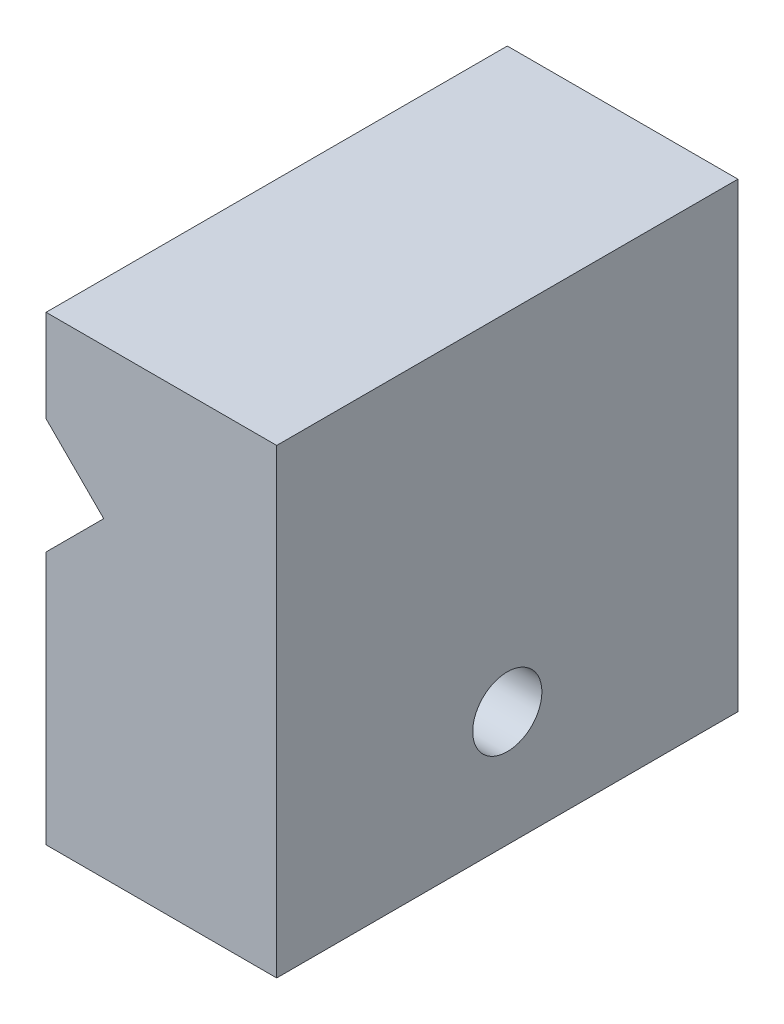
SolidWorks part; units mm, degrees
ref_plane "Plan de face" through (0, 0, 0) normal (0, 0, 1) x (1, 0, 0)
ref_plane "Plan de dessus" through (0, 0, 0) normal (0, 1, 0) x (1, 0, 0)
ref_plane "Plan de droite" through (0, 0, 0) normal (1, 0, 0) x (0, 0, -1)
sketch "Esquisse1" plane through (0, 0, 0) normal (0, 0, 1) x (1, 0, 0)
  line L1 (-5, -10) -> (5, -10)
  line L2 (-5, -10) -> (-5, 10)
  line L3 (-5, 10) -> (5, 10)
  line L4 (5, -10) -> (5, 10)
  line L5 (-5, -10) -> (5, 10) construction
  line L6 (-5, 10) -> (5, -10) construction
  point P0 (0, 0)
  dimension "D1" = 10
  dimension "D2" = 20
extrude "Extrusion1" add sketch "Esquisse1" along normal blind 20
sketch "Esquisse3" plane through (0, 0, 20) normal (0, 0, 1) x (1, 0, 0)
  line L0 (-5, 6) -> (-2.5, 3.5)
  line L1 (-5, 10) -> (-5, -10) construction
  line L2 (-2.5, 3.5) -> (-5, 1)
  line L3 (-5, -10) -> (5, -10) construction
  dimension "D1" = 5
  dimension "D2" = 13.5
extrude "Extrusion2" cut sketch "Esquisse3" against normal through all and the other way through all flip side to cut
sketch "Esquisse4" plane through (5, 0, 0) normal (1, 0, 0) x (0, 0, -1)
  line L0 (-20, -10) -> (0, -10) construction
  line L2 (0, -10) -> (0, 10) construction
  circle A0 centre (-10, -5) radius 1.5
  dimension "D4" = 3
  dimension "D5" = 5
  dimension "D6" = 10
extrude "Extrusion3" cut sketch "Esquisse4" against normal blind 40
